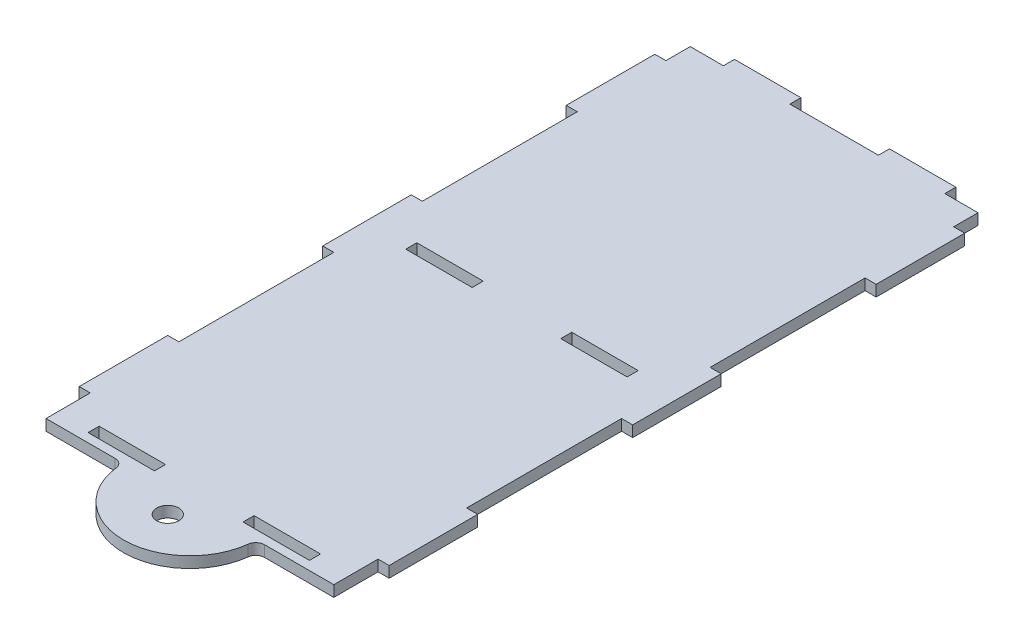
SolidWorks part; units mm, degrees
material "Mahogany"
ref_plane "Front" through (0, 0, 0) normal (0, 0, 1) x (1, 0, 0)
ref_plane "Top" through (0, 0, 0) normal (0, 1, 0) x (1, 0, 0)
ref_plane "Right" through (0, 0, 0) normal (1, 0, 0) x (0, 0, -1)
sketch "Sketch1" plane through (0, 0, 0) normal (0, 1, 0) x (1, 0, 0)
  line L0 (-32.5, -72.5) -> (-32.5, 72.5) construction
  line L1 (-35, -75) -> (35, -75) construction
  line L2 (-35, -75) -> (-35, 75) construction
  line L3 (-35, 75) -> (35, 75) construction
  line L4 (35, -75) -> (35, 75) construction
  line L5 (-35, -75) -> (35, 75) construction
  line L6 (-35, 75) -> (35, -75) construction
  line L7 (-32.5, 72.5) -> (32.5, 72.5) construction
  line L8 (32.5, -72.5) -> (32.5, 72.5) construction
  line L9 (-32.5, -72.5) -> (32.5, -72.5) construction
  line L10 (-35, -73) -> (35, -73) construction
  line L11 (-16.0465, 0) -> (20.7589, 0) construction
  line L12 (0, -12.0838) -> (0, 12.9514) construction
  line L13 (25, 1.25) -> (10, 1.25)
  line L14 (-25, -1.25) -> (-10, -1.25)
  line L15 (-25, -1.25) -> (-25, 1.25)
  line L16 (-25, 1.25) -> (-10, 1.25)
  line L17 (-10, -1.25) -> (-10, 1.25)
  line L18 (-25, -1.25) -> (-10, 1.25) construction
  line L19 (-25, 1.25) -> (-10, -1.25) construction
  line L20 (10, -1.25) -> (10, 1.25)
  line L21 (25, -1.25) -> (10, -1.25)
  line L22 (25, -1.25) -> (25, 1.25)
  line L31 (-25, -73) -> (-25, -70.5)
  line L32 (-25, -73) -> (-10, -73)
  line L33 (-10, -73) -> (-10, -70.5)
  line L34 (-25, -70.5) -> (-10, -70.5)
  line L35 (25, -70.5) -> (10, -70.5)
  line L36 (10, -73) -> (10, -70.5)
  line L37 (25, -73) -> (10, -73)
  line L38 (25, -73) -> (25, -70.5)
  line L39 (35, 45) -> (32.5, 45)
  line L40 (-35, 65) -> (-32.5, 65)
  line L41 (-35, 65) -> (-35, 45)
  line L42 (-35, 45) -> (-32.5, 45)
  line L43 (-32.5, 65) -> (-32.5, 45) construction
  line L44 (-35, 65) -> (-32.5, 45) construction
  line L45 (-35, 45) -> (-32.5, 65) construction
  line L46 (35, 65) -> (35, 45)
  line L47 (35, 65) -> (32.5, 65)
  line L48 (35, 10) -> (32.5, 10)
  line L49 (35, 10) -> (35, -10)
  line L50 (35, -10) -> (32.5, -10)
  line L51 (-35, 10) -> (-32.5, 10)
  line L52 (-35, 10) -> (-35, -10)
  line L53 (-35, -10) -> (-32.5, -10)
  line L54 (35, -45) -> (32.5, -45)
  line L55 (35, -45) -> (35, -65)
  line L56 (35, -65) -> (32.5, -65)
  line L57 (-35, -45) -> (-32.5, -45)
  line L58 (-35, -45) -> (-35, -65)
  line L59 (-35, -65) -> (-32.5, -65)
  line L62 (-32.5, 45) -> (-32.5, 10)
  line L63 (-32.5, -65) -> (-32.5, -75)
  line L64 (-32.5, -10) -> (-32.5, -45)
  line L68 (32.5, 45) -> (32.5, 10)
  line L69 (32.5, -10) -> (32.5, -45)
  line L70 (32.5, -65) -> (32.5, -75)
  line L72 (-15, -75) -> (-32.5, -75)
  line L73 (15, -75) -> (32.5, -75)
  line L74 (-35, 73) -> (35, 73) construction
  line L75 (-25, 70.5) -> (-25, 73)
  line L76 (-10, 70.5) -> (-10, 73)
  line L77 (-25, 73) -> (-10, 73)
  line L78 (25, 73) -> (10, 73)
  line L79 (10, 70.5) -> (10, 73)
  line L80 (25, 70.5) -> (25, 73)
  line L81 (-10, 70.5) -> (10, 70.5)
  line L82 (25, 70.5) -> (32.5, 70.5)
  line L83 (32.5, 70.5) -> (32.5, 65)
  line L84 (-25, 70.5) -> (-32.5, 70.5)
  line L85 (-32.5, 70.5) -> (-32.5, 65)
  arc A0 (-15, -75) -> (15, -75) centre (0, -75) ccw
  circle A1 centre (0, -80) radius 2.5
  point P0 (0, 0)
  point P16 (-17.5, 0)
  point P45 (-33.75, 55)
  dimension "D14" = 5
  dimension "D15" = 15
  dimension "D1" = 150
  dimension "D2" = 70
  dimension "D4" = 2
  dimension "D5" = 15
  dimension "D6" = 2.5
  dimension "D7" = 10
  dimension "D10" = 20
  dimension "D11" = 10
  dimension "D13" = 10
  dimension "D16" = 5
  dimension "D8" = 2
  dimension "D17" = 2
  dimension "D3" = 2.5
  dimension "D9" = 2
  dimension "D12" = 3
extrude "Boss-Extrude1" add sketch "Sketch1" along normal blind 2.5
fillet "Fillet1" radius 2 2 edges at (15, 1.25, 75) (-15, 1.25, 75)
